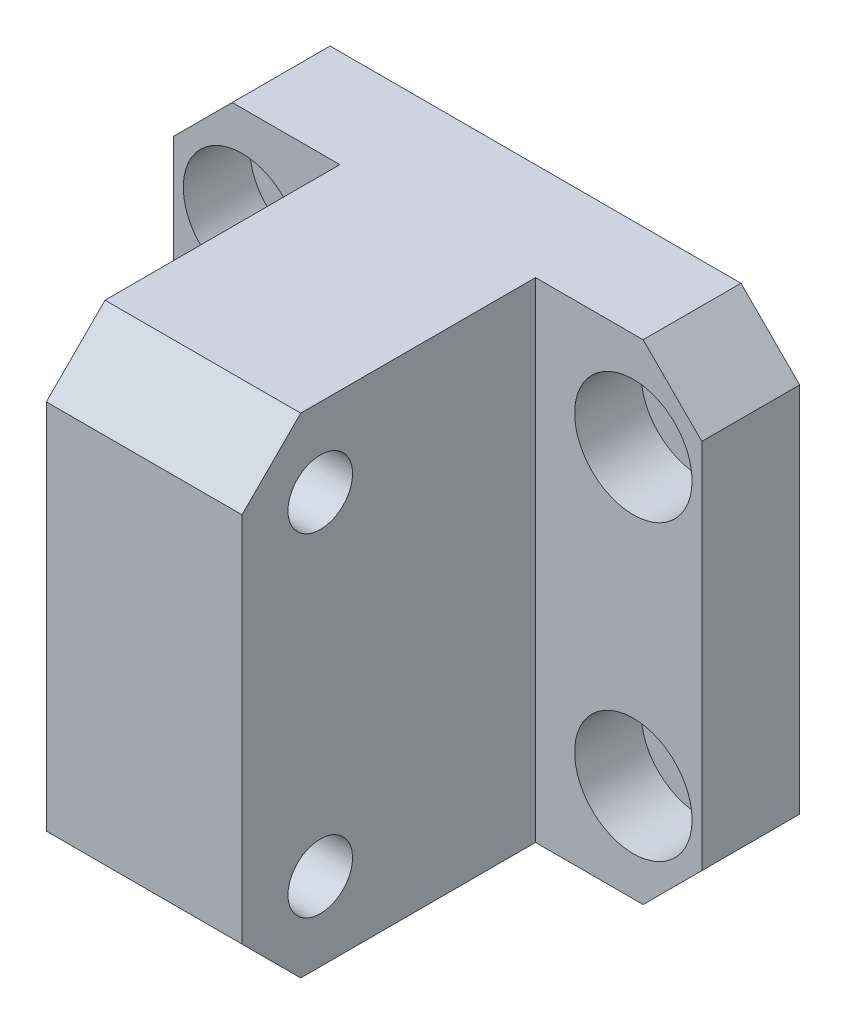
SolidWorks part; units mm, degrees
material "6061 Alloy"
ref_plane "Front Plane" through (0, 0, 0) normal (0, 0, 1) x (1, 0, 0)
ref_plane "Top Plane" through (0, 0, 0) normal (0, 1, 0) x (1, 0, 0)
ref_plane "Right Plane" through (0, 0, 0) normal (1, 0, 0) x (0, 0, -1)
sketch "Sketch1" plane through (0, 0, 0) normal (0, 0, 1) x (1, 0, 0)
  line L0 (0, -55) -> (0, 55) construction
  line L1 (-13.5, -12.5) -> (13.5, -12.5)
  line L2 (-13.5, -12.5) -> (-13.5, 12.5)
  line L3 (-13.5, 12.5) -> (13.5, 12.5)
  line L4 (13.5, -12.5) -> (13.5, 12.5)
  line L5 (-13.5, -12.5) -> (13.5, 12.5) construction
  line L6 (-13.5, 12.5) -> (13.5, -12.5) construction
  line L7 (55, 0) -> (-55, 0) construction
  point P0 (10, 7.5)
  point P9 (10, -7.5)
  point P11 (-10, -7.5)
  point P12 (-10, 7.5)
  dimension "D1" = 20
  dimension "D2" = 15
  dimension "D3" = 25
  dimension "D4" = 27
extrude "Boss-Extrude1" add sketch "Sketch1" along normal blind 5
sketch "Sketch2" plane through (0, 0, 5) normal (0, 0, 1) x (1, 0, 0)
  line L0 (13.5, 12.5) -> (-13.5, 12.5) construction
  line L1 (-5, -12.5) -> (5, -12.5)
  line L2 (-5, -12.5) -> (-5, 12.5)
  line L3 (-5, 12.5) -> (5, 12.5)
  line L4 (5, -12.5) -> (5, 12.5)
  line L5 (-5, -12.5) -> (5, 12.5) construction
  line L6 (-5, 12.5) -> (5, -12.5) construction
  point P0 (0, 0)
  dimension "D1" = 10
extrude "Boss-Extrude2" add sketch "Sketch2" along normal blind 15
hole_wizard "CBORE for M3 Hexagon socket head cap screws1" positions "Sketch3" profile "Sketch4" counterbore size "M3" standard "GB" end condition through all
sketch "Sketch3" plane through (0, 0, 5) normal (0, 0, 1) x (1, 0, 0)
  line L0 (55, 0) -> (-55, 0) construction
  line L1 (0, -55) -> (0, 55) construction
  point P0 (10, 7.5)
  point P5 (10, -7.5)
  point P8 (-10, -7.5)
  point P9 (-10, 7.5)
  dimension "D1" = 20
  dimension "D2" = 15
sketch "Sketch4" plane through (10, 7.5, 5) normal (1, 0, 0) x (0, -1, 0)
  line L0 (0, 0) -> (0, 5)
  line L1 (0, 5) -> (1.7, 5)
  line L3 (1.7, 5) -> (1.7, 3.4)
  line L4 (1.7, 3.4) -> (3, 3.4)
  line L5 (3, 3.4) -> (3, 0)
  line L7 (3, 0) -> (0, 0)
  line L11 (0, -6.35) -> (0, 107.95) construction
  dimension "Thru Hole Dia." = 3.4
  dimension "Thru Hole Depth" = 5
  dimension "C'Bore Dia." = 6
  dimension "C'Bore Depth" = 3.4
hole_wizard "M4 Tapped Hole1" positions "Sketch5" profile "Sketch6" tap size "M4" standard "GB" end condition through all
sketch "Sketch5" plane through (-5, 0, 0) normal (-1, 0, 0) x (0, 0, 1)
  line L0 (55, 0) -> (-55, 0) construction
  line L1 (20, 12.5) -> (20, -12.5) construction
  line L2 (20, 12.5) -> (5, 12.5) construction
  point P0 (16, 8.5)
  point P7 (16, -8.5)
  dimension "D1" = 4
  dimension "D2" = 4
sketch "Sketch6" plane through (-5, 8.5, 16) normal (0, 1, 0) x (0, 0, 1)
  line L0 (0, 0) -> (0, 18.5)
  line L1 (0, 18.5) -> (1.65, 18.5)
  line L2 (1.65, 18.5) -> (1.65, 0)
  line L5 (1.65, 0) -> (0, 0)
  line L11 (0, -6.35) -> (0, 107.95) construction
  dimension "Thru Tap Drill Dia." = 3.3
  dimension "Thru Tap Drill Depth" = 18.5
cosmetic thread "Hole Thread1"
cosmetic thread "Hole Thread2"
chamfer "Chamfer1" distance 3 angle 45 6 edges at (0, 12.5, 20) (0, -12.5, 20) (13.5, 12.5, 2.5) (13.5, -12.5, 2.5) (-13.5, -12.5, 2.5) (-13.5, 12.5, 2.5)
